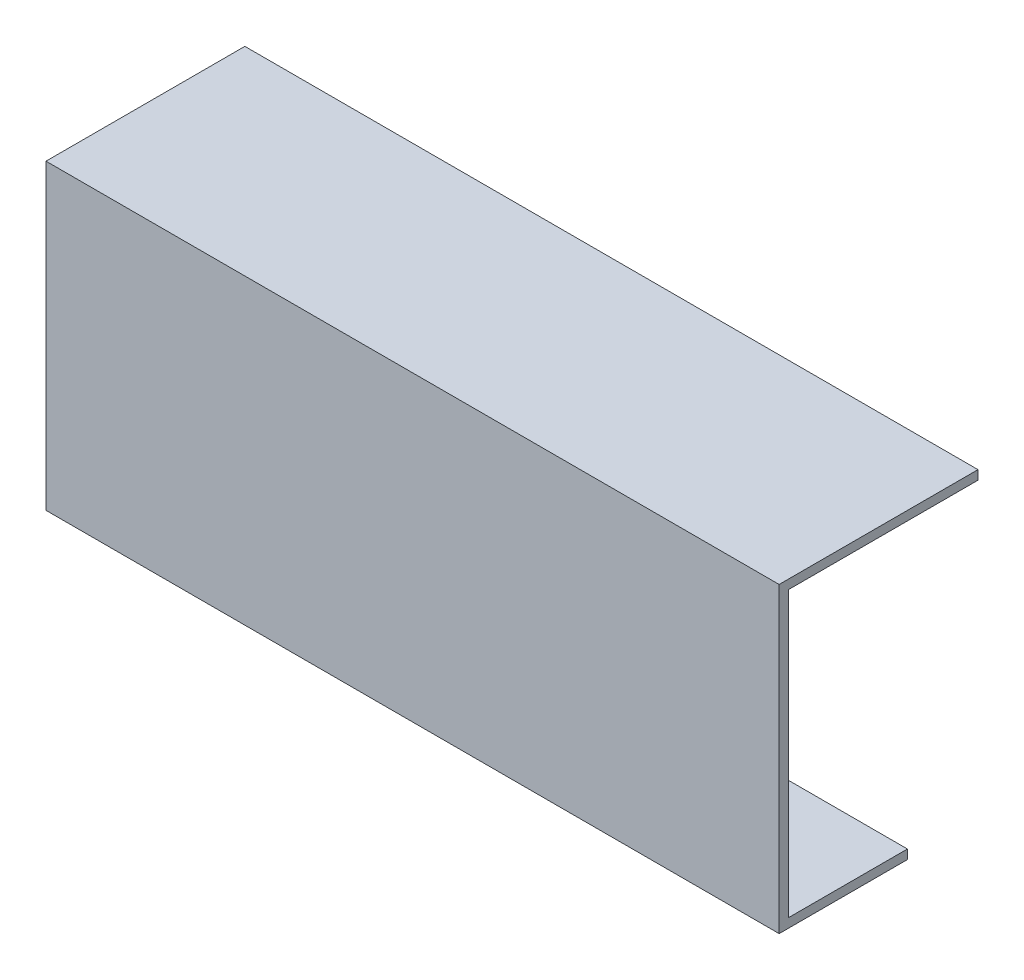
SolidWorks part; units mm, degrees
ref_plane "Front Plane" through (0, 0, 0) normal (0, 0, 1) x (1, 0, 0)
ref_plane "Top Plane" through (0, 0, 0) normal (0, 1, 0) x (1, 0, 0)
ref_plane "Right Plane" through (0, 0, 0) normal (1, 0, 0) x (0, 0, -1)
sketch "Sketch1" plane through (0, 0, 0) normal (0, 0, 1) x (1, 0, 0)
  line L1 (0, 0) -> (203.2, 0)
  line L2 (0, 0) -> (0, -83.82)
  line L3 (0, -83.82) -> (203.2, -83.82)
  line L4 (203.2, 0) -> (203.2, -83.82)
  dimension "D1" = 83.82
  dimension "D2" = 203.2
extrude "Boss-Extrude1" add sketch "Sketch1" along normal blind 55.118
sketch "Sketch2" plane through (203.2, 0, 0) normal (1, 0, 0) x (0, 0, -1)
  line L0 (-19.558, -83.82) -> (-19.558, -81.28)
  line L1 (-55.118, -83.82) -> (0, -83.82) construction
  line L2 (-19.558, -81.28) -> (-52.578, -81.28)
  line L3 (-52.578, -81.28) -> (-52.578, -2.54)
  line L4 (-52.578, -2.54) -> (0, -2.54)
  line L5 (0, -83.82) -> (0, 0) construction
  line L6 (0, -2.54) -> (0, -83.82)
  line L7 (0, -83.82) -> (-19.558, -83.82)
  line L8 (-55.118, -83.82) -> (-55.118, 0) construction
  line L9 (-55.118, 0) -> (0, 0) construction
  dimension "D1" = 35.56
  dimension "D2" = 2.54
  dimension "D3" = 2.54
  dimension "D4" = 2.54
extrude "Cut-Extrude1" cut sketch "Sketch2" against normal through all
